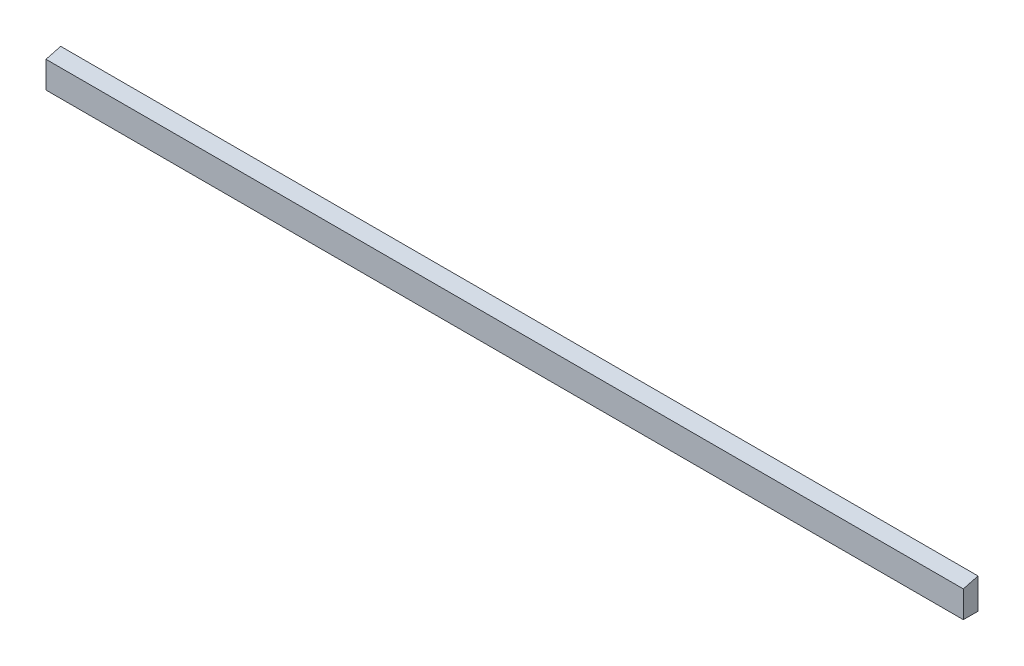
SolidWorks part; units mm, degrees
ref_plane "Front Plane" through (0, 0, 0) normal (0, 0, 1) x (1, 0, 0)
ref_plane "Top Plane" through (0, 0, 0) normal (0, 1, 0) x (1, 0, 0)
ref_plane "Right Plane" through (0, 0, 0) normal (1, 0, 0) x (0, 0, -1)
sketch "Sketch1" plane through (0, 0, 0) normal (1, 0, 0) x (0, 0, -1)
  line L0 (0, 0) -> (-18.2562, 0)
  line L1 (-18.2562, 0) -> (-18.2562, 33.2083)
  line L2 (-18.2562, 33.2083) -> (0, 38.1)
  line L3 (0, 38.1) -> (0, 0)
  dimension "D1" = 18.2562
  dimension "D2" = 38.1
  dimension "D3" = 75
extrude "Boss-Extrude1" add sketch "Sketch1" along normal blind 1143
